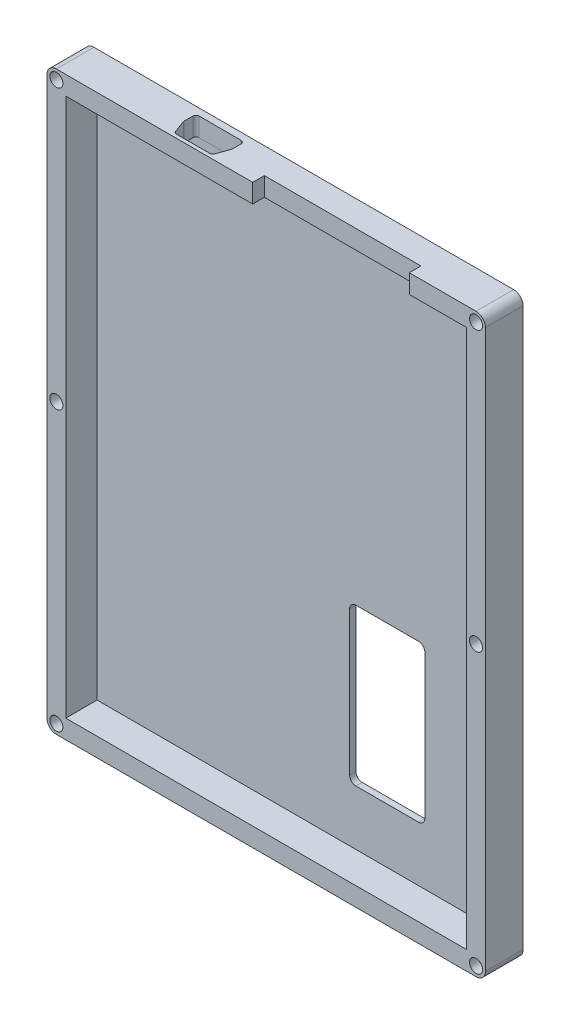
SolidWorks part; units mm, degrees
ref_plane "Front Plane" through (0, 0, 0) normal (0, 0, 1) x (1, 0, 0)
ref_plane "Top Plane" through (0, 0, 0) normal (0, 1, 0) x (1, 0, 0)
ref_plane "Right Plane" through (0, 0, 0) normal (1, 0, 0) x (0, 0, -1)
sketch "Sketch2" plane through (0, 0, 0) normal (0, 0, 1) x (1, 0, 0)
  line L1 (-33.5, 46) -> (33.5, 46)
  line L2 (-35, 44.5) -> (-35, -44.5)
  line L3 (-33.5, -46) -> (33.5, -46)
  line L4 (35, 44.5) -> (35, -44.5)
  line L5 (-35, 46) -> (35, -46) construction
  line L6 (-35, -46) -> (35, 46) construction
  arc A0 (33.5, 46) -> (35, 44.5) centre (33.5, 44.5) cw
  arc A1 (35, -44.5) -> (33.5, -46) centre (33.5, -44.5) cw
  arc A2 (-33.5, -46) -> (-35, -44.5) centre (-33.5, -44.5) cw
  arc A3 (-35, 44.5) -> (-33.5, 46) centre (-33.5, 44.5) cw
  point P0 (0, 0)
  dimension "D3" = 1.5
  dimension "D1" = 92
  dimension "D2" = 70
extrude "Boss-Extrude1" add sketch "Sketch2" along normal blind 1
sketch "Sketch3" plane through (0, 0, 1) normal (0, 0, 1) x (1, 0, 0)
  line L0 (0, 46) -> (0, -46) construction
  line L1 (33.5, 46) -> (-33.5, 46) construction
  line L2 (-33.5, -46) -> (33.5, -46) construction
  line L3 (-35, 0) -> (35, 0) construction
  line L4 (-35, 44.5) -> (-35, -44.5) construction
  line L5 (35, -44.5) -> (35, 44.5) construction
  line L6 (-35, -44.5) -> (35, -44.5) construction
  line L9 (-33.5, 46) -> (-33.5, -46) construction
  line L12 (-35, 44.5) -> (35, 44.5) construction
  line L13 (-33.5, 44.5) -> (-33.5, -44.5) construction
  line L14 (-32, 44.5) -> (-32, -44.5)
  line L15 (-35, 44.5) -> (-35, -44.5)
  line L16 (33.5, 44.5) -> (33.5, -44.5) construction
  line L17 (32, 44.5) -> (32, -44.5)
  line L18 (35, 44.5) -> (35, -44.5)
  arc A0 (-32, 44.5) -> (-35, 44.5) centre (-33.5, 44.5) ccw
  arc A1 (-35, -44.5) -> (-32, -44.5) centre (-33.5, -44.5) ccw
  arc A2 (32, 44.5) -> (35, 44.5) centre (33.5, 44.5) cw
  arc A3 (35, -44.5) -> (32, -44.5) centre (33.5, -44.5) cw
  point P18 (-33.5, 0)
  point P27 (33.5, 0)
extrude "Boss-Extrude2" add sketch "Sketch3" along normal blind 5
sketch "Sketch4" plane through (0, 0, 1) normal (0, 0, 1) x (1, 0, 0)
  line L0 (-33.5, 44.5) -> (-33.5, -44.5) construction
  line L1 (33.5, 44.5) -> (33.5, -44.5) construction
  line L2 (0, 46) -> (0, -46) construction
  line L3 (33.5, 46) -> (-33.5, 46) construction
  line L4 (-33.5, -46) -> (33.5, -46) construction
  line L5 (-33.5, 44.5) -> (33.5, 44.5) construction
  line L6 (-33.5, 46) -> (33.5, 46)
  line L7 (-33.5, 43) -> (33.5, 43)
  line L8 (-35, 0) -> (35, 0) construction
  line L9 (-35, 44.5) -> (-35, -44.5) construction
  line L10 (35, -44.5) -> (35, 44.5) construction
  line L11 (-33.5, -44.5) -> (33.5, -44.5) construction
  line L12 (-33.5, -46) -> (33.5, -46)
  line L13 (-33.5, -43) -> (33.5, -43)
  arc A0 (-33.5, 46) -> (-33.5, 43) centre (-33.5, 44.5) ccw
  arc A1 (33.5, 43) -> (33.5, 46) centre (33.5, 44.5) ccw
  arc A2 (-33.5, -46) -> (-33.5, -43) centre (-33.5, -44.5) cw
  arc A3 (33.5, -43) -> (33.5, -46) centre (33.5, -44.5) cw
  point P4 (0, 44.5)
  point P27 (0, -44.5)
extrude "Boss-Extrude3" add sketch "Sketch4" along normal blind 5
sketch "Sketch5" plane through (0, 46, 0) normal (0, 1, 0) x (1, 0, 0)
  line L0 (-33.5, -3) -> (22.9474, -3) construction
  line L1 (-33.5, -6) -> (-33.5, 0) construction
  line L3 (33.5, -3) -> (22.9474, -3) construction
  line L5 (-14.8957, -5.4287) -> (-9.5964, -5.4287)
  line L11 (-8.8961, -1.1127) -> (-15.5961, -1.1127)
  line L13 (-8.3961, -1.6127) -> (-8.3961, -3)
  line L20 (-8.4261, -3.1707) -> (-9.1265, -5.0994)
  line L22 (-12.2461, -1.1127) -> (-12.2461, -5.4287) construction
  line L23 (-16.066, -3.1707) -> (-15.3656, -5.0994)
  line L24 (-16.0961, -1.6127) -> (-16.0961, -3)
  line L25 (-16.0961, 0) -> (-16.0961, -10.9287) construction
  line L26 (33.5, 0) -> (-33.5, 0) construction
  line L27 (-8.3961, 0) -> (-8.3961, -10.9287) construction
  line L28 (33.5, -6) -> (33.5, 0) construction
  arc A1 (-16.0961, -3) -> (-16.066, -3.1707) centre (-15.5961, -3) ccw
  arc A2 (-16.0961, -1.6127) -> (-15.5961, -1.1127) centre (-15.5961, -1.6127) cw
  arc A3 (-8.8961, -1.1127) -> (-8.3961, -1.6127) centre (-8.8961, -1.6127) cw
  arc A4 (-8.3961, -3) -> (-8.4261, -3.1707) centre (-8.8961, -3) cw
  arc A5 (-9.1265, -5.0994) -> (-9.5964, -5.4287) centre (-9.5964, -4.9287) cw
  arc A6 (-14.8957, -5.4287) -> (-15.3656, -5.0994) centre (-14.8957, -4.9287) cw
  point P26 (-16.0961, -3.088)
  point P29 (-16.0961, -1.1127)
  point P32 (-8.3961, -1.1127)
  point P38 (-9.2461, -5.4287)
  point P41 (-15.2461, -5.4287)
  dimension "D2" = 0.5
  dimension "D3" = 0.5
  dimension "D1" = 6
  dimension "D5" = 7.7
extrude "Cut-Extrude3" cut sketch "Sketch5" against normal blind 10 contours A6 L5 A5 L20 A4 L13 A3 L11 A2 L24 A1 L23
sketch "Sketch7" plane through (0, 0, 0) normal (0, 0, -1) x (-1, 0, 0)
  line L0 (0, 46) -> (0, -46) construction
  line L1 (-33.5, 46) -> (33.5, 46) construction
  line L2 (33.5, -46) -> (-33.5, -46) construction
  line L3 (-35, 0) -> (35, 0) construction
  line L4 (-35, -44.5) -> (-35, 44.5) construction
  line L5 (35, 44.5) -> (35, -44.5) construction
  line L6 (-8.3229, -34.2229) -> (-8.3229, -46) construction
  line L7 (-19.3229, -9.2229) -> (-9.3229, -9.2229)
  line L8 (-20.3229, -10.2229) -> (-20.3229, -33.2229)
  line L9 (-19.3229, -34.2229) -> (-9.3229, -34.2229)
  line L10 (-8.3229, -10.2229) -> (-8.3229, -33.2229)
  line L11 (-20.3229, -9.2229) -> (-8.3229, -34.2229) construction
  line L12 (-20.3229, -34.2229) -> (-8.3229, -9.2229) construction
  line L13 (-8.3229, -9.2229) -> (-8.3229, 0) construction
  line L14 (-20.3229, -9.2229) -> (-20.3229, 0) construction
  line L15 (-20.3229, -21.7229) -> (-8.3229, -21.7229) construction
  line L16 (-20.3229, -34.2229) -> (-20.3229, -46) construction
  line L17 (-8.3229, -34.2229) -> (0, -34.2229) construction
  line L18 (-20.3229, -34.2229) -> (-35, -34.2229) construction
  line L19 (-8.3229, -9.2229) -> (0, -9.2229) construction
  line L20 (-20.3229, -9.2229) -> (-35, -9.2229) construction
  arc A0 (-8.3229, -33.2229) -> (-9.3229, -34.2229) centre (-9.3229, -33.2229) cw
  arc A1 (-19.3229, -34.2229) -> (-20.3229, -33.2229) centre (-19.3229, -33.2229) cw
  arc A2 (-20.3229, -10.2229) -> (-19.3229, -9.2229) centre (-19.3229, -10.2229) cw
  arc A3 (-9.3229, -9.2229) -> (-8.3229, -10.2229) centre (-9.3229, -10.2229) cw
  point P12 (-14.3229, -21.7229)
  point P17 (-20.3229, 0)
  point P28 (-14.3229, -21.2229)
  point P29 (0, 0)
  dimension "D3" = 1
  dimension "D1" = 12
  dimension "D2" = 25
extrude "Cut-Extrude2" cut sketch "Sketch7" against normal blind 10
sketch "Sketch10" plane through (0, 0, 6) normal (0, 0, 1) x (1, 0, 0)
  line L0 (-35, 0) -> (35, 0) construction
  line L1 (35, -44.5) -> (35, 44.5) construction
  line L2 (0, 46) -> (0, -46) construction
  line L3 (-33.5, -46) -> (33.5, -46) construction
  line L4 (-32, 43) -> (-32, 46) construction
  line L5 (33.5, 46) -> (-33.5, 46) construction
  line L6 (-32, 43) -> (-35, 43) construction
  line L7 (-35, 44.5) -> (-35, -44.5) construction
  line L8 (-32, -43) -> (-35, -43) construction
  line L9 (-32, -43) -> (-32, -46) construction
  line L10 (32, 43) -> (35, 43) construction
  line L11 (32, 43) -> (32, 46) construction
  line L12 (32, -43) -> (32, -46) construction
  line L13 (32, -43) -> (35, -43) construction
  line L14 (-33.5, 44.5) -> (-33.5, -44.5) construction
  line L15 (33.5, 44.5) -> (33.5, -44.5) construction
  point P6 (0, 0)
  point P12 (0, 0)
  point P35 (-33.5, 0)
hole_wizard "Tap Drill for #3-56 Tap1" positions "Sketch28" profile "Sketch25" hole size "#3-56" standard "ANSI Inch" end condition through all
sketch "Sketch28" plane through (0, 0, 6) normal (0, 0, 1) x (1, 0, 0)
  point P0 (-33.5, 44.5)
  point P3 (-33.5, 0)
  point P6 (-33.5, -44.5)
  point P9 (33.5, -44.5)
  point P12 (33.4997, 0)
  point P14 (33.5, 44.5)
sketch "Sketch25" plane through (-33.5, 44.5, 6) normal (1, 0, 0) x (0, -1, 0)
  line L0 (0, 0) -> (0, 6)
  line L1 (0, 6) -> (1.0414, 6)
  line L2 (1.0414, 6) -> (1.0414, 0)
  line L5 (1.0414, 0) -> (0, 0)
  line L11 (0, -6.35) -> (0, 107.95) construction
  dimension "Thru Hole Dia." = 2.0828
  dimension "Thru Hole Depth" = 6
sketch "Sketch29" plane through (0, 46, 0) normal (0, 1, 0) x (1, 0, 0)
  line L1 (33.5, -6) -> (33.5, 0) construction
  line L2 (10.3426, -4.135) -> (10.3426, -6) construction
  line L8 (-2.1574, -4.135) -> (22.8426, -4.135)
  line L10 (33.5, -6) -> (-33.5, -6) construction
  line L11 (-2.1574, -4.135) -> (-2.1574, -6)
  line L14 (22.8426, -4.135) -> (22.8426, -6)
  line L15 (22.8426, -6) -> (-2.1574, -6)
  line L16 (-8.7763, -4.135) -> (33.5, -4.135) construction
  line L17 (-8.4261, -3.1707) -> (-9.1265, -5.0994) construction
  dimension "D1" = 25
extrude "Cut-Extrude4" cut sketch "Sketch29" against normal blind 10
